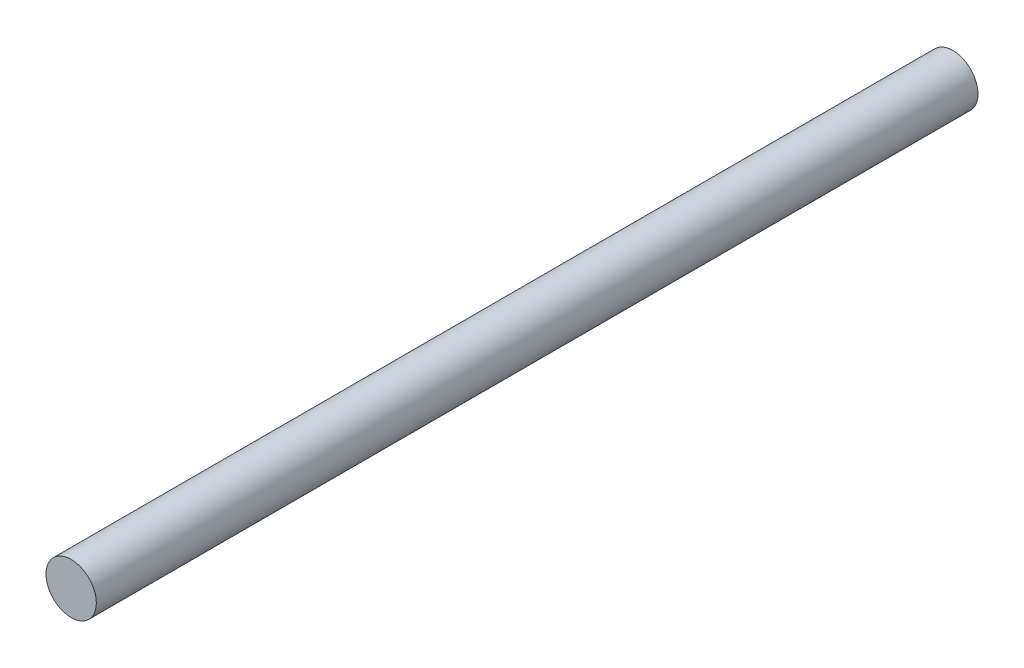
SolidWorks part; units mm, degrees
ref_plane "Plan de face" through (0, 0, 0) normal (0, 0, 1) x (1, 0, 0)
ref_plane "Plan de dessus" through (0, 0, 0) normal (0, 1, 0) x (1, 0, 0)
ref_plane "Plan de droite" through (0, 0, 0) normal (1, 0, 0) x (0, 0, -1)
sketch "Esquisse1" plane through (0, 0, 0) normal (0, 0, 1) x (1, 0, 0)
  circle A0 centre (0, 0) radius 4
  dimension "D1" = 8
extrude "Boss.-Extru.1" add sketch "Esquisse1" along normal blind 140
